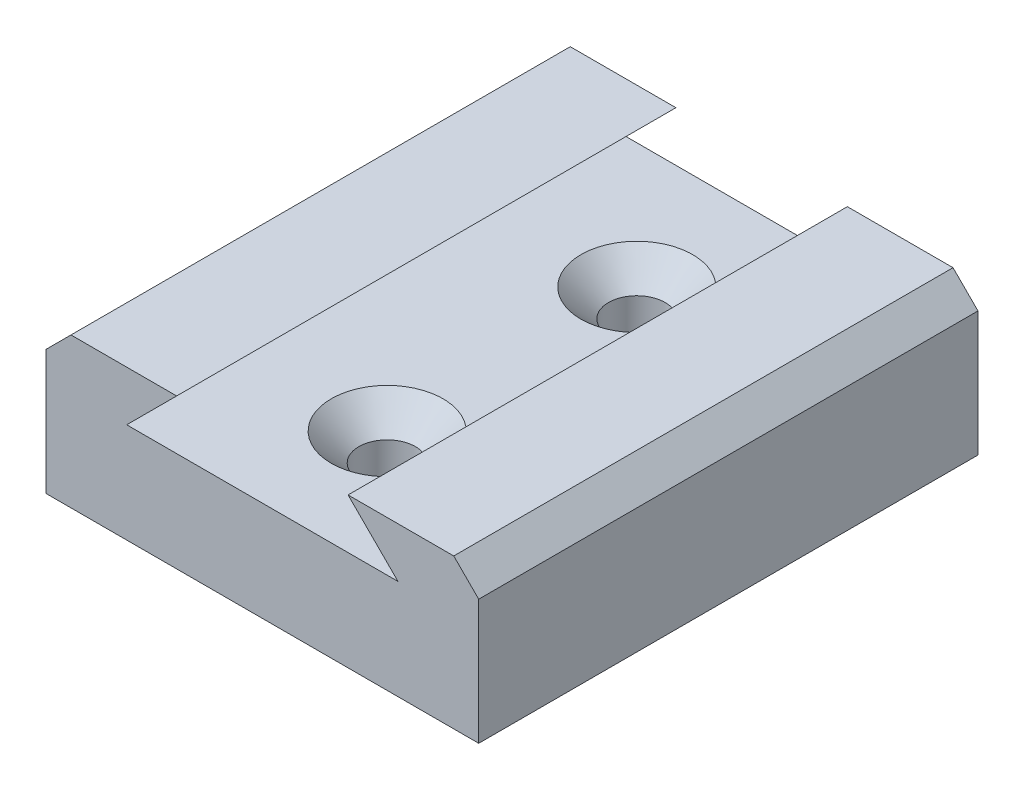
SolidWorks part; units mm, degrees
ref_plane "Front Plane" through (0, 0, 0) normal (0, 0, 1) x (1, 0, 0)
ref_plane "Top Plane" through (0, 0, 0) normal (0, 1, 0) x (1, 0, 0)
ref_plane "Right Plane" through (0, 0, 0) normal (1, 0, 0) x (0, 0, -1)
sketch "Sketch2" plane through (0, 0, 0) normal (0, 0, 1) x (1, 0, 0)
  line L0 (-13, 0) -> (13, 0)
  line L1 (13, 0) -> (13, 7.5)
  line L2 (13, 7.5) -> (11.5, 9)
  line L3 (11.5, 9) -> (5.15, 9)
  line L4 (5.15, 9) -> (8.15, 6)
  line L5 (8.15, 6) -> (-8.15, 6)
  line L6 (-8.15, 6) -> (-5.15, 9)
  line L7 (-5.15, 9) -> (-11.5, 9)
  line L8 (-11.5, 9) -> (-13, 7.5)
  line L9 (-13, 7.5) -> (-13, 0)
  point P0 (0, 0)
  point P12 (0, 6)
  dimension "D1" = 16.3
  dimension "D2" = 45
  dimension "D3" = 3
  dimension "D4" = 45
  dimension "D5" = 26
  dimension "D6" = 1.5
  dimension "D7" = 1.5
  dimension "D8" = 6
extrude "Boss-Extrude1" add sketch "Sketch2" along normal blind 30
sketch "Sketch7" plane through (0, 6, 0) normal (0, 1, 0) x (1, 0, 0)
  line L10 (0, -7.5) -> (0, -22.5) construction
  line L12 (0, -7.5) -> (0, 0) construction
  line L14 (0, -22.5) -> (0, -30) construction
  line L15 (8.15, -30) -> (-8.15, -30) construction
  point P21 (0, -7.5)
  point P23 (0, -22.5)
  dimension "D1" = 15
hole_wizard "CSK for M3 Hex Socket Countersunk Cap Screw2" positions "Sketch7" profile "Sketch8" countersink size "M3" standard "ISO" end condition up to next
sketch "Sketch8" plane through (0, 6, 7.5) normal (1, 0, 0) x (0, 0, 1)
  line L0 (0, 0) -> (0, 6)
  line L1 (0, 6) -> (1.7, 6)
  line L2 (1.7, 6) -> (1.7, 1.66)
  line L3 (1.7, 1.66) -> (3.36, 0)
  line L5 (3.36, 0) -> (0, 0)
  line L6 (-1.7, 1.66) -> (-3.36, 0) construction
  line L11 (0, -6.35) -> (0, 107.95) construction
  dimension "Thru Hole Dia." = 3.4
  dimension "Thru Hole Depth" = 6
  dimension "Near C'Sink Dia." = 6.72
  dimension "Near C'Sink Angle" = 90
